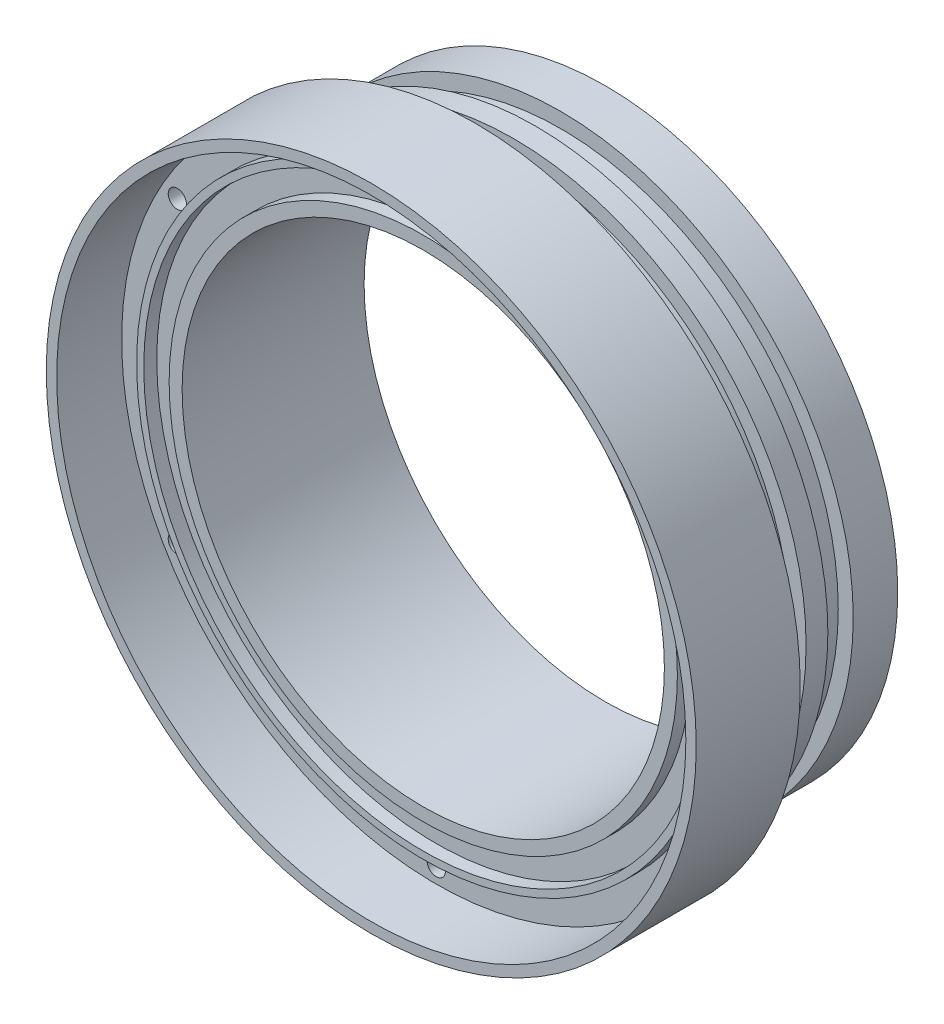
SolidWorks part; units mm, degrees
material "6063-O"
ref_plane "Front Plane" through (0, 0, 0) normal (0, 0, 1) x (1, 0, 0)
ref_plane "Top Plane" through (0, 0, 0) normal (0, 1, 0) x (1, 0, 0)
ref_plane "Right Plane" through (0, 0, 0) normal (1, 0, 0) x (0, 0, -1)
sketch "Sketch1" plane through (0, 0, 0) normal (0, 0, 1) x (1, 0, 0)
  circle A0 centre (0, 0) radius 50
extrude "Boss-Extrude1" add sketch "Sketch1" against normal blind 28 separate body
sketch "Sketch4" plane through (0, 0, -28) normal (0, 0, -1) x (-1, 0, 0)
  circle A0 centre (0, 0) radius 45
  circle A1 centre (0, 0) radius 53.8706
extrude "Cut-Extrude1" cut sketch "Sketch4" against normal blind 20
sketch "Sketch5" plane through (0, 0, -28) normal (0, 0, -1) x (-1, 0, 0)
  circle A0 centre (0, 0) radius 37.1
  circle A1 centre (0, 0) radius 45
  circle A2 centre (0, 0) radius 45
  dimension "D2" = 7.9
  dimension "D1" = 0
extrude "Cut-Extrude2" cut sketch "Sketch5" against normal blind 46.3831 contours A0
sketch "Sketch6" plane through (0, 0, 0) normal (0, 0, 1) x (1, 0, 0)
  circle A0 centre (0, 0) radius 49.9975
  circle A1 centre (0, 0) radius 52
  circle A2 centre (0, 0) radius 37.1
  circle A3 centre (0, 0) radius 39.1
  circle A4 centre (0, 0) radius 43
  dimension "D1" = 2
  dimension "D2" = 3.9
extrude "Cut-Extrude3" cut sketch "Sketch6" against normal blind 2 contours A4 A3
sketch "Sketch7" plane through (0, 0, 0) normal (0, 0, 1) x (1, 0, 0)
  line L0 (0, 0) -> (0, 65.442) construction
  circle A0 centre (0, 0) radius 46 construction
  circle A2 centre (0, 0) radius 50
  circle A3 centre (0, 0) radius 50
  circle A4 centre (0, 46) radius 1.4
  circle A5 centre (39.8372, 23) radius 1.4
  circle A6 centre (39.8372, -23) radius 1.4
  circle A7 centre (0, -46) radius 1.4
  circle A8 centre (-39.8372, -23) radius 1.4
  circle A9 centre (-39.8372, 23) radius 1.4
  point P0 (35.1631, 29.6573)
  point P25 (0, 0)
  dimension "D2" = 6
  dimension "D3" = 92
  dimension "D1" = 0
extrude "Cut-Extrude4" cut sketch "Sketch7" against normal blind 7 contours A4 | A5 | A6 | A7 | A8 | A9
sketch "Sketch8" plane through (0, 0, 0) normal (0, 0, 1) x (1, 0, 0)
  circle A0 centre (0, 0) radius 46 construction
  circle A1 centre (0, 0) radius 50
  circle A2 centre (0, 0) radius 50
  dimension "D1" = 0
extrude "Extrude-Thin1" add sketch "Sketch8" along normal blind 8 thin thin type one direction reverse wall 1.6
sketch "Sketch9" plane through (0, 0, 0) normal (0, 0, 1) x (1, 0, 0)
  line L0 (-47.7679, 7.7965) -> (-47.1659, 6.2151)
  line L2 (-39.6703, -12.4204) -> (-54.9271, -17.1971) construction
  line L3 (-34.7929, -33.6454) -> (-35.2002, -32.0031)
  line L4 (-17.132, 45.2665) -> (-18.2005, 43.9544)
  line L5 (-46.5342, 13.3088) -> (-45.3156, 14.4828)
  line L6 (30.636, 37.47) -> (28.9654, 37.7393)
  line L7 (-11.7414, 46.9542) -> (-10.1153, 46.4858)
  line L8 (47.7679, -7.7965) -> (47.1659, -6.2151)
  line L9 (34.7929, 33.6454) -> (35.2002, 32.0031)
  line L10 (17.132, -45.2665) -> (18.2005, -43.9544)
  line L11 (46.5342, -13.3088) -> (45.3156, -14.4828)
  line L12 (-30.636, -37.47) -> (-28.9654, -37.7393)
  line L13 (11.7414, -46.9542) -> (10.1153, -46.4858)
  arc A0 (-47.7679, 7.7965) -> (-34.7929, -33.6454) centre (0, 0) ccw
  arc A3 (-43.8796, 4.4039) -> (-33.5335, -28.6411) centre (0, 0) ccw
  arc A4 (-17.132, 45.2665) -> (-46.5342, 13.3088) centre (0, 0) ccw
  arc A5 (-18.1259, 40.2028) -> (-41.5707, 14.7203) centre (0, 0) ccw
  arc A6 (30.636, 37.47) -> (-11.7414, 46.9542) centre (0, 0) ccw
  arc A7 (25.7537, 35.7988) -> (-8.0372, 43.3614) centre (0, 0) ccw
  arc A8 (47.7679, -7.7965) -> (34.7929, 33.6454) centre (0, 0) ccw
  arc A9 (43.8796, -4.4039) -> (33.5335, 28.6411) centre (0, 0) ccw
  arc A10 (17.132, -45.2665) -> (46.5342, -13.3088) centre (0, 0) ccw
  arc A11 (18.1259, -40.2028) -> (41.5707, -14.7203) centre (0, 0) ccw
  arc A12 (-30.636, -37.47) -> (11.7414, -46.9542) centre (0, 0) ccw
  arc A13 (-25.7537, -35.7988) -> (8.0372, -43.3614) centre (0, 0) ccw
  circle A14 centre (0, 0) radius 44.1
  circle A15 centre (0, 0) radius 48.4
  spline S0 degree 2 poles (-47.1659, 6.2151) (-45.896, 4.7791) (-43.8796, 4.4039) knots 0 0 0 1 1 1
  spline S1 degree 2 poles (-35.2002, -32.0031) (-34.976, -30.0992) (-33.5335, -28.6411) knots 0 0 0 1 1 1
  spline S2 degree 2 poles (-18.2005, 43.9544) (-18.8092, 42.1367) (-18.1259, 40.2028) knots 0 0 0 1 1 1
  spline S3 degree 2 poles (-45.3156, 14.4828) (-43.5547, 15.2405) (-41.5707, 14.7203) knots 0 0 0 1 1 1
  spline S4 degree 2 poles (28.9654, 37.7393) (27.0868, 37.3576) (25.7537, 35.7988) knots 0 0 0 1 1 1
  spline S5 degree 2 poles (-10.1153, 46.4858) (-8.5787, 45.3397) (-8.0372, 43.3614) knots 0 0 0 1 1 1
  spline S6 degree 2 poles (47.1659, -6.2151) (45.896, -4.7791) (43.8796, -4.4039) knots 0 0 0 1 1 1
  spline S7 degree 2 poles (35.2002, 32.0031) (34.976, 30.0992) (33.5335, 28.6411) knots 0 0 0 1 1 1
  spline S8 degree 2 poles (18.2005, -43.9544) (18.8092, -42.1367) (18.1259, -40.2028) knots 0 0 0 1 1 1
  spline S9 degree 2 poles (45.3156, -14.4828) (43.5547, -15.2405) (41.5707, -14.7203) knots 0 0 0 1 1 1
  spline S10 degree 2 poles (-28.9654, -37.7393) (-27.0868, -37.3576) (-25.7537, -35.7988) knots 0 0 0 1 1 1
  spline S11 degree 2 poles (10.1153, -46.4858) (8.5787, -45.3397) (8.0372, -43.3614) knots 0 0 0 1 1 1
  point P54 (0, 0)
  circle M3 centre (-39.8372, 23) radius 1.4
  circle M4 centre (-39.8372, -23) radius 1.4
  circle M5 centre (0, -46) radius 1.4
  circle M6 centre (39.8372, -23) radius 1.4
  circle M7 centre (39.8372, 23) radius 1.4
  circle M8 centre (0, 46) radius 1.4
  circle M9 centre (0, 0) radius 48.4
  dimension "D1" = 6
extrude "Cut-Extrude5" cut sketch "Sketch9" against normal blind 2 contours L12 S10 A14 S1 L3 M4 M9 | M4 | A14 L2 A15 L3 S1 | L2 A3 S0 L0 M9 | L13 S11 A13 S10 L12 M9 | S11 L13 L10 S8 A14 M9 M5 | M5 | M3 | S3 L5 L0 S0 A14 M9 M3 | M8 | S5 L7 L4 S2 A14 M9 M8 | L7 S5 A7 S4 L6 M9 | L5 S3 A5 S2 L4 M9 | L9 S7 A9 S6 L8 M9 | L11 S9 A11 S8 L10 M9 | M7 | S7 L9 L6 S4 A14 M9 M7 | M6 | S9 L11 L8 S6 A14 M9 M6
sketch "Sketch10" plane through (0, 0, 0) normal (0, 1, 0) x (1, 0, 0)
  line L0 (-45, 8) -> (-45, 10) construction
  line L1 (-45, 28) -> (-45, 8) construction
  line L2 (0, 0) -> (0, 41.951)
  line L3 (-45, 10) -> (-42.7, 10)
  line L4 (-45, 10) -> (-45, 13.9)
  line L5 (-45, 13.9) -> (-42.7, 13.9)
  line L6 (-42.7, 10) -> (-42.7, 13.9)
  line L7 (-45, 13.7514) -> (-45, 17.2514)
  line L9 (-45, 17.2514) -> (-42.7, 17.2514)
  line L10 (-45, 17.2514) -> (-45, 21.1514)
  line L11 (-45, 21.1514) -> (-42.7, 21.1514)
  line L12 (-42.7, 17.2514) -> (-42.7, 21.1514)
revolve "Cut-Revolve1" cut sketch "Sketch10" angle 360 about L2
sketch "Sketch11" plane through (0, 0, -28) normal (0, 0, -1) x (-1, 0, 0)
  line L0 (0, 36.7494) -> (0, 45) construction
  circle A0 centre (0, 40.8747) radius 1.3563
  circle A2 centre (0, 0) radius 45 construction
  circle A3 centre (40.8747, 0) radius 1.3563
  circle A4 centre (0, -40.8747) radius 1.3563
  circle A5 centre (-40.8747, 0) radius 1.3563
  point P17 (0, 0)
  dimension "D1" = 4
extrude "Cut-Extrude7" cut sketch "Sketch11" against normal blind 5
